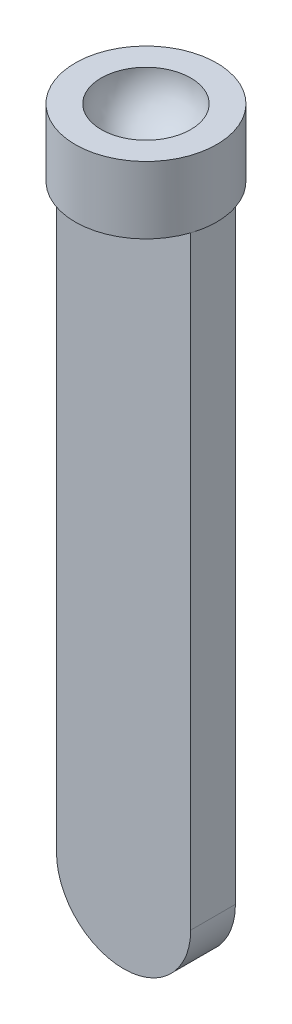
SolidWorks part; units mm, degrees
ref_plane "Front Plane" through (0, 0, 0) normal (0, 0, 1) x (1, 0, 0)
ref_plane "Top Plane" through (0, 0, 0) normal (0, 1, 0) x (1, 0, 0)
ref_plane "Right Plane" through (0, 0, 0) normal (1, 0, 0) x (0, 0, -1)
sketch "Sketch1" plane through (0, 0, 0) normal (0, 0, 1) x (1, 0, 0)
  line L2 (-15, -75) -> (-15, 75)
  line L3 (-15, 75) -> (15, 75)
  line L4 (15, -75) -> (15, 75)
  line L5 (-15, -75) -> (15, 75) construction
  line L6 (-15, 75) -> (15, -75) construction
  arc A0 (-15, -75) -> (15, -75) centre (0, -75) ccw
  point P0 (0, 0)
  dimension "D1" = 150
  dimension "D2" = 30
extrude "Boss-Extrude1" add sketch "Sketch1" along normal mid plane 10
sketch "Sketch4" plane through (0, 75, 0) normal (0, 1, 0) x (1, 0, 0)
  circle A0 centre (0, 0) radius 15.8114
extrude "Boss-Extrude2" add sketch "Sketch4" against normal blind 15
sketch "Sketch6" plane through (0, 0, 0) normal (0, 0, 1) x (1, 0, 0)
  line L0 (15.8114, 75) -> (-15.8114, 75) construction
  line L1 (0, 75) -> (0, 65) construction
  line L2 (0, 75) -> (10, 75)
  line L4 (0, 75) -> (0, 65)
  arc A0 (10, 75) -> (0, 65) centre (0, 75) cw
  dimension "D1" = 20
revolve "Cut-Revolve3" cut sketch "Sketch6" angle 360 about L1
